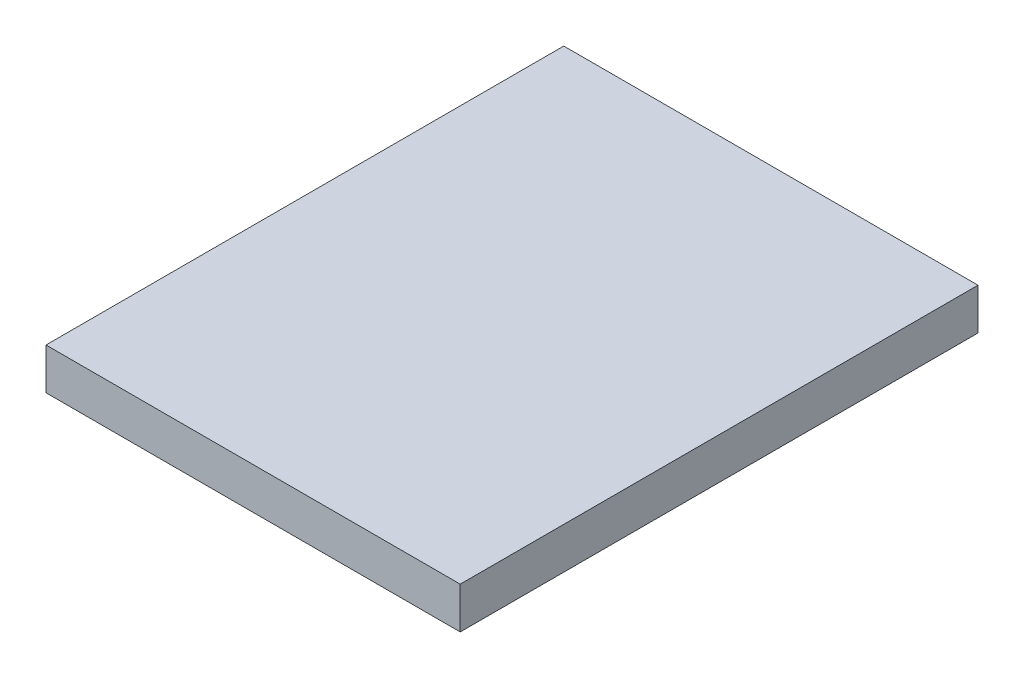
SolidWorks part; units mm, degrees
ref_plane "Front Plane" through (0, 0, 0) normal (0, 0, 1) x (1, 0, 0)
ref_plane "Top Plane" through (0, 0, 0) normal (0, 1, 0) x (1, 0, 0)
ref_plane "Right Plane" through (0, 0, 0) normal (1, 0, 0) x (0, 0, -1)
sketch "Sketch1" plane through (0, 0, 0) normal (0, 1, 0) x (1, 0, 0)
  line L0 (-61.3757, 51.5873) -> (38.6243, 51.5873)
  line L1 (38.6243, 51.5873) -> (38.6243, -73.4127)
  line L2 (-61.3757, 51.5873) -> (-61.3757, -73.4127)
  line L3 (-61.3757, -73.4127) -> (38.6243, -73.4127)
  dimension "D1" = 100
  dimension "D2" = 125
extrude "Boss-Extrude1" add sketch "Sketch1" along normal blind 10
